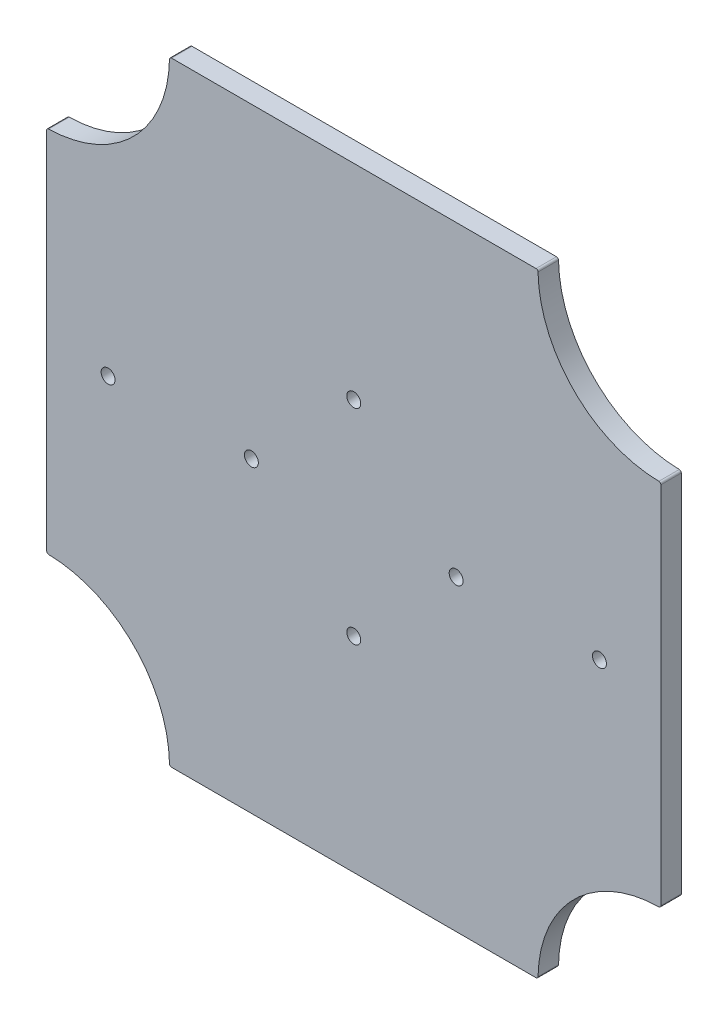
SolidWorks part; units mm, degrees
material "Plastique personnalisé"
ref_plane "Plan de face" through (0, 0, 0) normal (0, 0, 1) x (1, 0, 0)
ref_plane "Plan de dessus" through (0, 0, 0) normal (0, 1, 0) x (1, 0, 0)
ref_plane "Plan de droite" through (0, 0, 0) normal (1, 0, 0) x (0, 0, -1)
sketch "Esquisse1" plane through (0, 0, 0) normal (0, 0, 1) x (1, 0, 0)
  line L0 (75, 75) -> (-75, -75) construction
  line L1 (-75, 75) -> (75, 75)
  line L2 (-75, 75) -> (-75, -75)
  line L3 (-75, -75) -> (75, -75)
  line L4 (75, 75) -> (75, -75)
  line L5 (75, -75) -> (-75, 75) construction
  dimension "D1" = 150
  dimension "D2" = 150
extrude "Boss.-Extru.1" add sketch "Esquisse1" along normal blind 5
sketch "Esquisse2" plane through (0, 0, 5) normal (0, 0, 1) x (1, 0, 0)
  line L0 (75, 75) -> (-75, 75) construction
  line L1 (75, -75) -> (75, 75) construction
  line L2 (45, 75) -> (75, 75)
  line L3 (75, 75) -> (75, 45)
  line L4 (75, -75) -> (45, -75)
  line L5 (75, -45) -> (75, -75)
  line L6 (-75, -75) -> (-75, -45)
  line L7 (-45, -75) -> (-75, -75)
  line L8 (-75, 75) -> (-45, 75)
  line L9 (-75, 45) -> (-75, 75)
  arc A0 (45, 75) -> (75, 45) centre (75, 75) ccw
  arc A1 (75, -45) -> (45, -75) centre (75, -75) ccw
  arc A2 (-45, -75) -> (-75, -45) centre (-75, -75) ccw
  arc A3 (-75, 45) -> (-45, 75) centre (-75, 75) ccw
  point P20 (0, 0)
  point P21 (0, 0)
  dimension "D1" = 30
  dimension "D2" = 4
extrude "Enlèv. mat.-Extru.1" cut sketch "Esquisse2" against normal up to surface (5 mm away) up to face at (0, 0, 0)
hole_wizard "Dégagement M31" positions "Esquisse3" profile "Esquisse4" hole size "M3" standard "ISO" end condition up to next
sketch "Esquisse3" plane through (0, 0, 0) normal (0, 0, -1) x (-1, 0, 0)
  line L0 (-75, -45) -> (-75, 45) construction
  line L1 (75, 45) -> (75, -45) construction
  point P0 (0, 25)
  point P2 (0, -25)
  point P4 (60, 0)
  point P6 (25, 0)
  point P8 (-25, 0)
  point P10 (-60, 0)
  dimension "D1" = 25
  dimension "D2" = 25
  dimension "D3" = 25
  dimension "D4" = 25
  dimension "D5" = 15
  dimension "D6" = 15
sketch "Esquisse4" plane through (0, 25, 0) normal (1, 0, 0) x (0, 1, 0)
  line L0 (0, 0) -> (0, 5)
  line L1 (0, 5) -> (1.7, 5)
  line L2 (1.7, 5) -> (1.7, 0)
  line L5 (1.7, 0) -> (0, 0)
  line L11 (0, -6.35) -> (0, 107.95) construction
  dimension "Diamètre du perçage jusqu'au prochain" = 3.4
  dimension "Profondeur du perçage jusqu'au prochain" = 5
fillet "Congé1" radius 0.5 8 edges at (75, 45, 2.5) (45, 75, 2.5) (-45, 75, 2.5) (-75, 45, 2.5) (-75, -45, 2.5) (-45, -75, 2.5) (75, -45, 2.5) (45, -75, 2.5)
